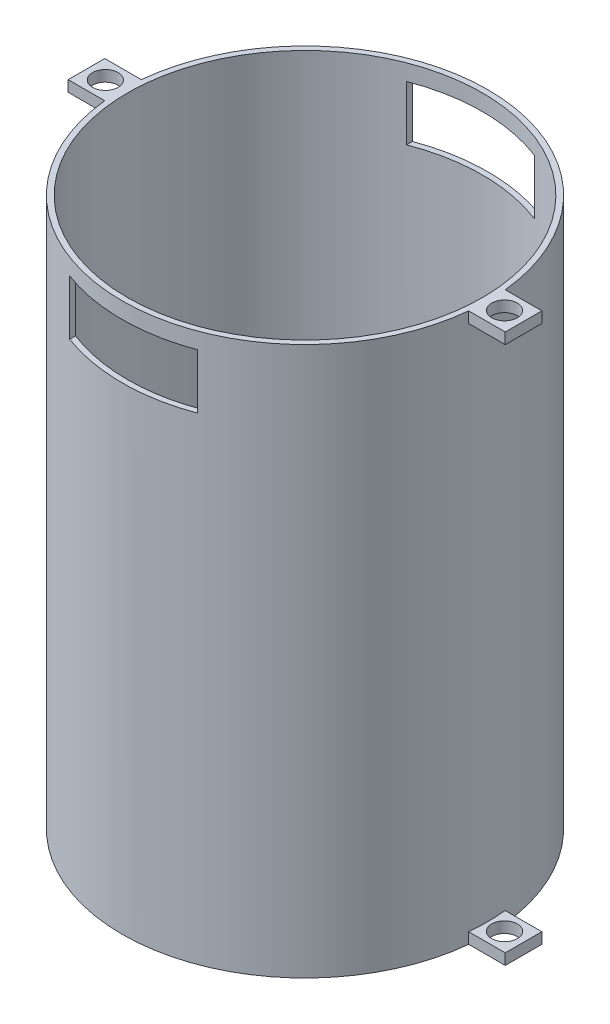
SolidWorks part; units mm, degrees
ref_plane "Front Plane" through (0, 0, 0) normal (0, 0, 1) x (1, 0, 0)
ref_plane "Top Plane" through (0, 0, 0) normal (0, 1, 0) x (1, 0, 0)
ref_plane "Right Plane" through (0, 0, 0) normal (1, 0, 0) x (0, 0, -1)
sketch "Sketch2" plane through (0, 0, 0) normal (0, 1, 0) x (1, 0, 0)
  circle A0 centre (0, 0) radius 50
  dimension "D1" = 100
extrude "Boss-Extrude1" add sketch "Sketch2" along normal blind 150
sketch "Sketch3" plane through (0, 150, 0) normal (0, 1, 0) x (1, 0, 0)
  circle A0 centre (0, 0) radius 48
  dimension "D1" = 96
extrude "Cut-Extrude1" cut sketch "Sketch3" against normal blind 150
sketch "Sketch4" plane through (0, 150, 0) normal (0, 1, 0) x (1, 0, 0)
  line L1 (-59.7494, 5) -> (-49.7494, 5)
  line L2 (-59.7494, 5) -> (-59.7494, -5)
  line L3 (-59.7494, -5) -> (-49.7494, -5)
  line L4 (-49.7494, 5) -> (-49.7494, -5)
  line L5 (59.7494, 5) -> (49.7494, 5)
  line L6 (59.7494, 5) -> (59.7494, -5)
  line L7 (59.7494, -5) -> (49.7494, -5)
  line L8 (49.7494, 5) -> (49.7494, -5)
  circle A0 centre (0, 0) radius 50 construction
  dimension "D1" = 10
  dimension "D2" = 10
  dimension "D3" = 10
  dimension "D4" = 10
extrude "Boss-Extrude2" add sketch "Sketch4" against normal blind 3 contours L6 L5 L8 L7
sketch "Sketch5" plane through (0, 150, 0) normal (0, 1, 0) x (1, 0, 0)
  line L1 (-59.7494, 5) -> (-49.7494, 5)
  line L2 (-59.7494, 5) -> (-59.7494, -5)
  line L3 (-59.7494, -5) -> (-49.7494, -5)
  line L4 (-49.7494, 5) -> (-49.7494, -5)
  arc A0 (49.7494, 5) -> (49.7494, -5) centre (0, 0) ccw construction
  dimension "D1" = 10
  dimension "D2" = 10
extrude "Boss-Extrude3" add sketch "Sketch5" against normal blind 3 contours L2 L1 L4 L3
sketch "Sketch6" plane through (0, 0, 0) normal (0, -1, 0) x (-1, 0, 0)
  line L1 (-108.3015, 6.3476) -> (-98.3015, 6.3476)
  line L2 (-108.3015, 6.3476) -> (-108.3015, -3.6524)
  line L3 (-108.3015, -3.6524) -> (-98.3015, -3.6524)
  line L4 (-98.3015, 6.3476) -> (-98.3015, -3.6524)
  line L5 (11.1973, 6.3476) -> (1.1973, 6.3476)
  line L6 (11.1973, 6.3476) -> (11.1973, -3.6524)
  line L7 (11.1973, -3.6524) -> (1.1973, -3.6524)
  line L8 (1.1973, 6.3476) -> (1.1973, -3.6524)
  dimension "D1" = 10
  dimension "D2" = 10
  dimension "D3" = 10
  dimension "D4" = 10
extrude "Boss-Extrude4" [suppressed] add sketch "Sketch6" against normal blind 3 contours L6 L5 L8 L7
sketch "Sketch7" plane through (0, 0, 0) normal (0, 1, 0) x (1, 0, 0)
  line L1 (-59.7494, -5) -> (-49.7494, -5)
  line L2 (-59.7494, -5) -> (-59.7494, 5)
  line L3 (-59.7494, 5) -> (-49.7494, 5)
  line L4 (-49.7494, -5) -> (-49.7494, 5)
  dimension "D1" = 10
  dimension "D2" = 10
extrude "Boss-Extrude5" add sketch "Sketch7" along normal blind 3 contours L2 L1 L4 L3
sketch "Sketch8" plane through (0, 0, 0) normal (0, -1, 0) x (-1, 0, 0)
  line L1 (-59.7494, -5) -> (-49.7494, -5)
  line L2 (-59.7494, -5) -> (-59.7494, 5)
  line L3 (-59.7494, 5) -> (-49.7494, 5)
  line L4 (-49.7494, -5) -> (-49.7494, 5)
extrude "Boss-Extrude6" add sketch "Sketch8" against normal blind 3
sketch "Sketch9" plane through (0, 0, 0) normal (0, -1, 0) x (1, 0, 0)
  circle A0 centre (54.5452, 0) radius 3.5
  dimension "D1" = 7
extrude "Cut-Extrude2" cut sketch "Sketch9" against normal blind 200
sketch "Sketch10" plane through (0, 0, 0) normal (0, -1, 0) x (-1, 0, 0)
  circle A0 centre (54.586, 0) radius 3.5
extrude "Cut-Extrude3" cut sketch "Sketch10" against normal blind 200
sketch "Sketch11" plane through (0, 0, 0) normal (0, 0, 1) x (1, 0, 0)
  line L1 (-17.5, 145.5723) -> (17.5, 145.5723)
  line L2 (-17.5, 145.5723) -> (-17.5, 130.5723)
  line L3 (-17.5, 130.5723) -> (17.5, 130.5723)
  line L4 (17.5, 145.5723) -> (17.5, 130.5723)
  line L5 (-17.5, 145.5723) -> (17.5, 130.5723) construction
  line L6 (-17.5, 130.5723) -> (17.5, 145.5723) construction
  point P0 (0, 138.0723)
  dimension "D1" = 15
  dimension "D2" = 35
extrude "Cut-Extrude4" cut sketch "Sketch11" against normal blind 150 and the other way blind 150
sketch "Sketch12" plane through (0, 150, 0) normal (0, 1, 0) x (1, 0, 0)
  circle A0 centre (0, 0) radius 48.5
  dimension "D1" = 97
extrude "Cut-Extrude5" cut sketch "Sketch12" against normal blind 150
